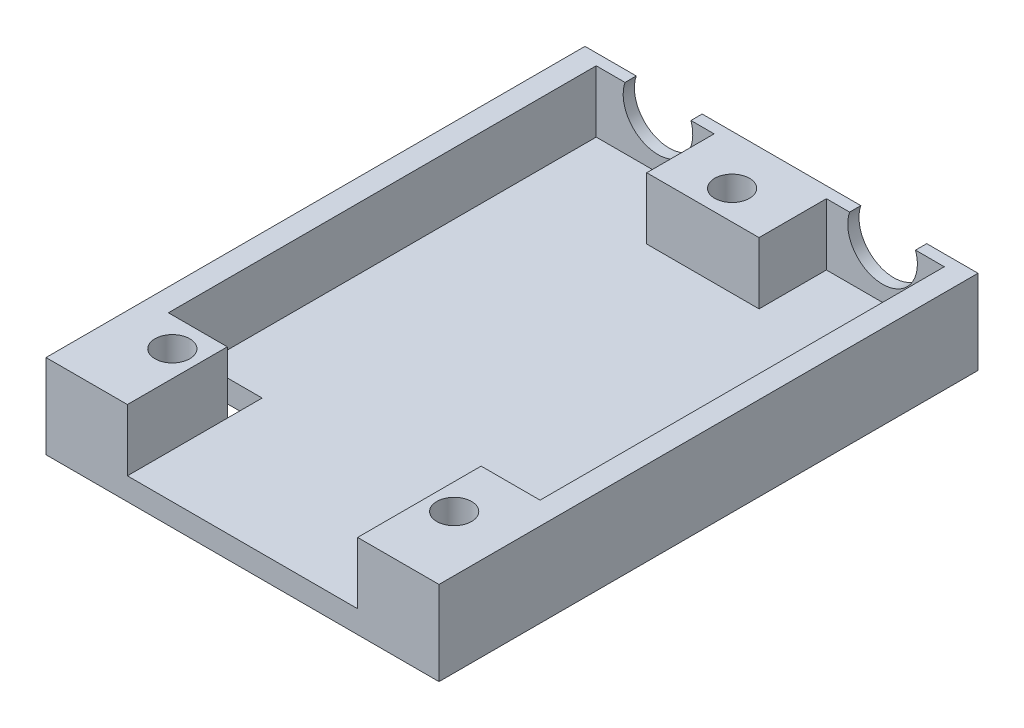
SolidWorks part; units mm, degrees
ref_plane "Front Plane" through (0, 0, 0) normal (0, 0, 1) x (1, 0, 0)
ref_plane "Top Plane" through (0, 0, 0) normal (0, 1, 0) x (1, 0, 0)
ref_plane "Right Plane" through (0, 0, 0) normal (1, 0, 0) x (0, 0, -1)
sketch "Sketch1" plane through (0, 0, 0) normal (0, 1, 0) x (1, 0, 0)
  line L1 (-17.5, 24) -> (17.5, 24)
  line L2 (-17.5, 24) -> (-17.5, -24)
  line L3 (-17.5, -24) -> (17.5, -24)
  line L4 (17.5, 24) -> (17.5, -24)
  line L5 (-44.2539, 0) -> (44.2539, 0) construction
  line L6 (0, -44.7868) -> (0, 44.7868) construction
  dimension "D2" = 35
  dimension "D1" = 48
  dimension "D3" = 24
  dimension "D4" = 17.5
extrude "Boss-Extrude1" add sketch "Sketch1" along normal blind 2
sketch "Sketch2" plane through (0, 2, 0) normal (0, 1, 0) x (1, 0, 0)
  line L1 (-15.5, 23) -> (15.5, 23)
  line L2 (-15.5, 23) -> (-15.5, -21)
  line L3 (-15.5, -21) -> (15.5, -21)
  line L4 (15.5, 23) -> (15.5, -21)
  line L6 (17.5, -24) -> (17.5, 24) construction
  line L7 (-17.5, -24) -> (17.5, -24) construction
  line M5 (-17.5, 24) -> (-17.5, -24)
  line M6 (-17.5, -24) -> (17.5, -24)
  line M7 (17.5, -24) -> (17.5, 24)
  line M8 (17.5, 24) -> (-17.5, 24)
  dimension "D1" = 2
  dimension "D2" = 3
  dimension "D3" = 31
  dimension "D4" = 44
extrude "Boss-Extrude2" add sketch "Sketch2" along normal blind 5.5 contours L1 L4 L3 L2 M8 M5 M6 M7
sketch "Sketch3" plane through (0, 2, 0) normal (0, 1, 0) x (1, 0, 0)
  line L0 (-15.5, 23) -> (15.5, 23) construction
  line L1 (-5, 23) -> (5, 23)
  line L2 (-5, 23) -> (-5, 17)
  line L3 (-5, 17) -> (5, 17)
  line L4 (5, 23) -> (5, 17)
  line L5 (15.5, 23) -> (15.5, -21) construction
  line L7 (-15.5, -21) -> (-10.25, -21)
  line L8 (-15.5, -21) -> (-15.5, -13)
  line L9 (-15.5, -13) -> (-10.25, -13)
  line L10 (-10.25, -21) -> (-10.25, -13)
  line L11 (15.5, -21) -> (10.25, -21)
  line L12 (15.5, -21) -> (15.5, -13)
  line L13 (15.5, -13) -> (10.25, -13)
  line L14 (10.25, -21) -> (10.25, -13)
  dimension "D1" = 10
  dimension "D2" = 6
  dimension "D3" = 10.5
  dimension "D4" = 5.25
  dimension "D5" = 5.25
  dimension "D6" = 8
  dimension "D7" = 8
extrude "Boss-Extrude3" add sketch "Sketch3" along normal blind 5.5
sketch "Sketch4" plane through (0, 0, 24) normal (0, 0, 1) x (1, 0, 0)
  line L0 (-17.5, 7.5) -> (17.5, 7.5) construction
  line L1 (-10.25, 7.5) -> (10.25, 7.5)
  line L2 (-10.25, 7.5) -> (-10.25, 2)
  line L3 (-10.25, 2) -> (10.25, 2)
  line L4 (10.25, 7.5) -> (10.25, 2)
  line L5 (-17.5, 7.5) -> (-17.5, 0) construction
  line L6 (17.5, 7.5) -> (17.5, 0) construction
  dimension "D1" = 7.25
  dimension "D2" = 7.25
  dimension "D3" = 5.5
extrude "Cut-Extrude1" cut sketch "Sketch4" against normal up to surface (3 mm away) up to face at (0, 4.75, 21)
sketch "Sketch5" plane through (0, 0, 0) normal (0, -1, 0) x (1, 0, 0)
  line L0 (44.2539, 0) -> (-44.2539, 0) construction
  line L1 (-2.45, 8.5) -> (2.45, 8.5)
  line L2 (-2.45, 8.5) -> (-2.45, 3.6)
  line L3 (-2.45, 3.6) -> (2.45, 3.6)
  line L4 (2.45, 8.5) -> (2.45, 3.6)
  line L5 (-2.45, -3.6) -> (2.45, -3.6)
  line L6 (-2.45, -3.6) -> (-2.45, -8.5)
  line L7 (-2.45, -8.5) -> (2.45, -8.5)
  line L8 (2.45, -3.6) -> (2.45, -8.5)
  line L9 (17.5, 24) -> (17.5, -24) construction
  dimension "D1" = 4.9
  dimension "D2" = 7.2
  dimension "D3" = 3.6
  dimension "D4" = 15.05
  dimension "D5" = 15.05
extrude "Boss-Extrude4" add sketch "Sketch5" along normal blind 2
sketch "Sketch6" plane through (0, 0, -24) normal (0, 0, -1) x (-1, 0, 0)
  line L0 (-17.5, 7.5) -> (17.5, 7.5) construction
  line L3 (-17.5, 7.5) -> (-17.5, 0) construction
  arc A0 (-7.0657, 7.5) -> (-12.9343, 7.5) centre (-10, 6.5) cw
  arc A1 (12.9343, 7.5) -> (7.0657, 7.5) centre (10, 6.5) cw
  line M3 (17.5, 7.5) -> (-17.5, 7.5)
  dimension "D1" = 20
  dimension "D3" = 3.1
  dimension "D4" = 3.1
  dimension "D2" = 7.5
  dimension "D5" = 1
  dimension "D6" = 1
extrude "Cut-Extrude2" cut sketch "Sketch6" against normal blind 2 contours A0 M3 | A1 M3
sketch "Sketch7" plane through (0, 7.5, 0) normal (0, 1, 0) x (1, 0, 0)
  line L1 (-15.5, -12) -> (-10.25, -12)
  line L2 (-15.5, -12) -> (-15.5, -15.1)
  line L3 (-15.5, -15.1) -> (-10.25, -15.1)
  line L4 (-10.25, -12) -> (-10.25, -15.1)
  line L5 (-10.25, -24) -> (-10.25, -13) construction
  line L6 (-17.5, -24) -> (-10.25, -24) construction
  dimension "D1" = 3.1
  dimension "D2" = 5.25
  dimension "D3" = 8.9
extrude "Cut-Extrude3" cut sketch "Sketch7" against normal up to surface (7.5 mm away)
sketch "Sketch8" plane through (0, 0, 0) normal (0, 1, 0) x (1, 0, 0)
  line L0 (0, -44.7868) -> (0, 44.7868) construction
  line L1 (10.25, -24) -> (17.5, -24) construction
  line L2 (7.0657, 24) -> (-7.0657, 24) construction
  line L4 (-17.5, -24) -> (-10.25, -24) construction
  circle A0 centre (-12.55, -17.7) radius 1.55
  circle A1 centre (12.55, -17.7) radius 1.55
  circle A2 centre (0, 19.6) radius 1.55
  dimension "D1" = 3.1
  dimension "D7" = 3.1
  dimension "D8" = 3.1
  dimension "D2" = 6.3
  dimension "D3" = 25.1
  dimension "D4" = 6.3
  dimension "D5" = 12.55
  dimension "D6" = 4.4
extrude "Cut-Extrude4" cut sketch "Sketch8" along direction (0, 1, 0) on the side against the normal blind 5.5 from surface at 7.5 starting at face at (-14.0461, 7.5, -1.975)
sketch "Sketch9" plane through (0, 0, 0) normal (0, 1, 0) x (1, 0, 0)
  line L0 (-35.1135, -20.6) -> (29.9959, -20.6) construction
  line L1 (-7.0657, 23) -> (-5, 23) construction
  line L2 (-35.1135, 21.9) -> (32.5575, 21.9) construction
  point P4 (-6.0329, 23)
  dimension "D1" = 43.6
  dimension "D2" = 42.5
equation "\"fWidth\"=35"
equation "\"D2@Sketch1\"=\"fWidth\""
equation "\"fLength\"= 48"
equation "\"D1@Sketch1\"=\"fLength\""
equation "\"D3@Sketch1\"=\"fLength\"/2"
equation "\"D4@Sketch1\"=\"fWidth\"/2"
equation "\"wThickness\"=2"
equation "\"D1@Sketch2\"=\"wThickness\""
equation "\"D3@Sketch2\"=\"fWidth\"- 2* \"wThickness\""
equation "\"D4@Sketch2\"=\"fLength\"- 2 *\"wThickness\""
equation "\"wHeight\"= 5.5"
equation "\"D1@Boss-Extrude2\"=\"wHeight\""
equation "\"D3@Sketch3\"=(\"fWidth\"- 2 *\"wThickness\" - 10)/2"
equation "\"D4@Sketch5\"=(\"fWidth\"- 4.9)/2"
equation "\"D5@Sketch5\"=(\"fWidth\"- 4.9)/2"
equation "\"D3@Sketch4\"=\"wHeight\""
